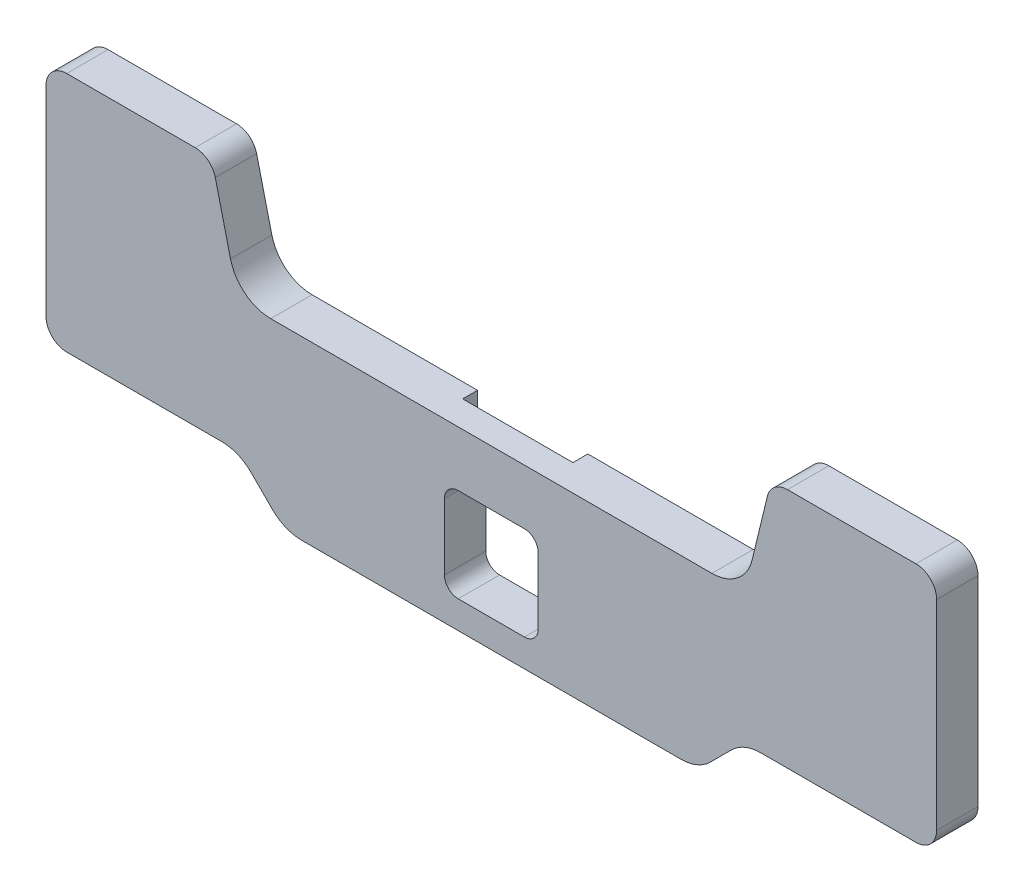
SolidWorks part; units mm, degrees
material "Q355"
ref_plane "前视基准面" through (0, 0, 0) normal (0, 0, 1) x (1, 0, 0)
ref_plane "上视基准面" through (0, 0, 0) normal (0, 1, 0) x (1, 0, 0)
ref_plane "右视基准面" through (0, 0, 0) normal (1, 0, 0) x (0, 0, -1)
sketch "草图1" plane through (0, 0, 0) normal (0, 0, 1) x (1, 0, 0)
  line L0 (-323, 208) -> (-323, 33)
  line L1 (-323, 208) -> (-203, 208)
  line L2 (-323, 33) -> (-183, 33)
  line L3 (-183, 33) -> (-150, 0)
  line L4 (-150, 0) -> (150, 0)
  line L5 (160, 128) -> (-160, 128)
  line L7 (0, 128) -> (0, 0) construction
  line L9 (183, 33) -> (150, 0)
  line L10 (323, 33) -> (183, 33)
  line L11 (323, 208) -> (203, 208)
  line L12 (323, 208) -> (323, 33)
  line L13 (-203, 208) -> (-189.1544, 150.9273)
  line L14 (203, 208) -> (189.1544, 150.9273)
  arc A4 (-189.1544, 150.9273) -> (-160, 128) centre (-160, 158) ccw
  arc A5 (189.1544, 150.9273) -> (160, 128) centre (160, 158) cw
  dimension "D8" = 30
  dimension "D9" = 175
  dimension "D2" = 135
  dimension "D3" = 323
  dimension "D4" = 150
  dimension "D5" = 33
  dimension "D6" = 128
  dimension "D7" = 160
  dimension "D10" = 120
extrude "凸台-拉伸1" add sketch "草图1" along normal blind 30
fillet "圆角1" radius 15 6 edges at (323, 208, 15) (323, 33, 15) (-323, 33, 15) (-323, 208, 15) (203, 208, 15) (-203, 208, 15)
fillet "圆角2" radius 30 4 edges at (150, 0, 15) (183, 33, 15) (-150, 0, 15) (-183, 33, 15)
sketch "草图2" plane through (0, 0, 30) normal (0, 0, 1) x (1, 0, 0)
  line L0 (0, 0) -> (0, 128) construction
  line L1 (-24, 88) -> (24, 88)
  line L2 (-34, 78) -> (-34, 30)
  line L3 (-24, 20) -> (24, 20)
  line L4 (34, 78) -> (34, 30)
  line L5 (160, 128) -> (-160, 128) construction
  line L6 (-137.5736, 0) -> (137.5736, 0) construction
  arc A0 (-34, 30) -> (-24, 20) centre (-24, 30) ccw
  arc A1 (24, 20) -> (34, 30) centre (24, 30) ccw
  arc A2 (24, 88) -> (34, 78) centre (24, 78) cw
  arc A3 (-24, 88) -> (-34, 78) centre (-24, 78) ccw
  dimension "D1" = 10
  dimension "D2" = 68
  dimension "D3" = 20
  dimension "D4" = 68
extrude "切除-拉伸1" cut sketch "草图2" against normal blind 30
sketch "草图3" plane through (0, 0, 0) normal (1, 0, 0) x (0, 0, -1)
  line L0 (0, 130) -> (-12, 130)
  line L1 (0, 48) -> (0, 193) construction
  line L2 (-12, 130) -> (0, 110)
  line L3 (0, 130) -> (0, 110)
  line L4 (0, 0) -> (-30, 0) construction
  dimension "D1" = 12
  dimension "D2" = 20
  dimension "D3" = 130
extrude "切除-拉伸2" cut sketch "草图3" against normal mid plane 80
